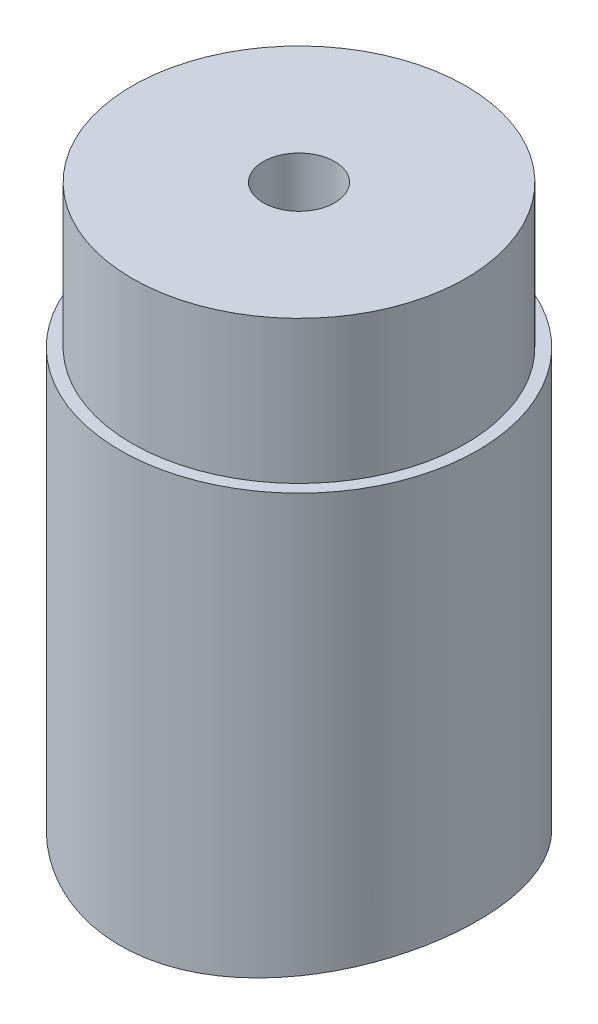
SolidWorks part; units mm, degrees
material "1.4000 (X6Cr13)"
ref_plane "Alzado" through (0, 0, 0) normal (0, 0, 1) x (1, 0, 0)
ref_plane "Planta" through (0, 0, 0) normal (0, 1, 0) x (1, 0, 0)
ref_plane "Vista lateral" through (0, 0, 0) normal (1, 0, 0) x (0, 0, -1)
sketch "Croquis1" plane through (0, 0, 0) normal (0, 0, 1) x (1, 0, 0)
  line L0 (0, 0) -> (0, 13.8429) construction
  line L1 (7, 24) -> (7, 18)
  line L2 (7, 18) -> (7.5, 18)
  line L3 (7.5, 18) -> (7.5, 0)
  line L4 (7.5, 0) -> (1.5, 0)
  line L5 (1.5, 0) -> (1.5, 24)
  line L6 (1.5, 24) -> (7, 24)
  dimension "D1" = 7.5
  dimension "D2" = 3
  dimension "D3" = 18
  dimension "D4" = 7
  dimension "D5" = 6
revolve "Revolución1" add sketch "Croquis1" angle 360 about L0
sketch "Croquis2" plane through (0, 0, 0) normal (1, 0, 0) x (0, 0, -1)
  line L0 (-7.5, 0) -> (7.5, 0)
  arc A0 (-7.5, 0) -> (7.5, 0) centre (0, -30.5941) cw
  dimension "D1" = 31.5
extrude "Cortar-Extruir1" cut sketch "Croquis2" against normal through all both and the other way through all contours L0 A0
